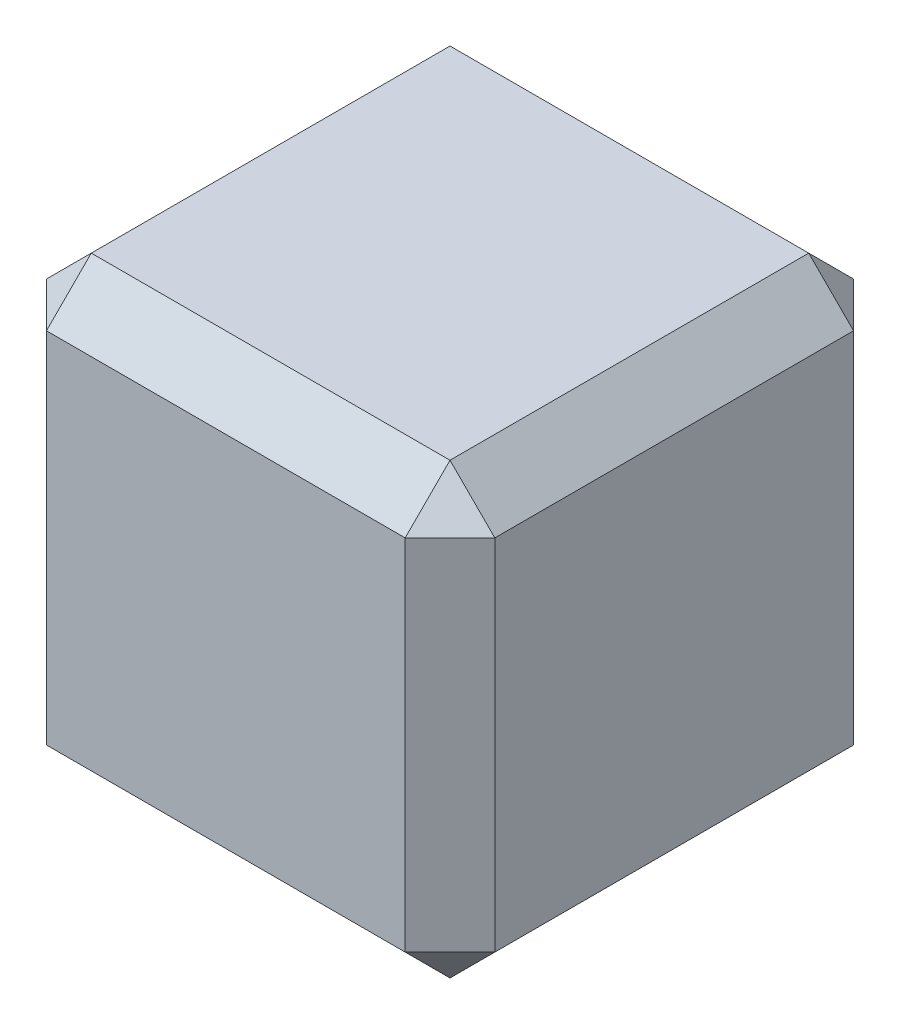
SolidWorks part; units mm, degrees
material "ABS"
ref_plane "Front Plane" through (0, 0, 0) normal (0, 0, 1) x (1, 0, 0)
ref_plane "Top Plane" through (0, 0, 0) normal (0, 1, 0) x (1, 0, 0)
ref_plane "Right Plane" through (0, 0, 0) normal (1, 0, 0) x (0, 0, -1)
sketch "Esboço1" plane through (0, 0, 0) normal (0, 1, 0) x (1, 0, 0)
  line L1 (-5, -5) -> (5, -5)
  line L2 (-5, -5) -> (-5, 5)
  line L3 (-5, 5) -> (5, 5)
  line L4 (5, -5) -> (5, 5)
  line L5 (-5, -5) -> (5, 5) construction
  line L6 (-5, 5) -> (5, -5) construction
  point P0 (0, 0)
  dimension "D1" = 10
extrude "Ressalto-extrusão1" add sketch "Esboço1" along normal mid plane 10
shell "Casca2" thickness 1
chamfer "Chanfro1" distance 1 angle 45 12 edges at (-5, 0, -5) (0, -5, -5) (-5, -5, 0) (-5, 0, 5) (0, -5, 5) (5, 0, 5) (5, -5, 0) (5, 0, -5) (0, 5, 5) (-5, 5, 0) (0, 5, -5) (5, 5, 0)
